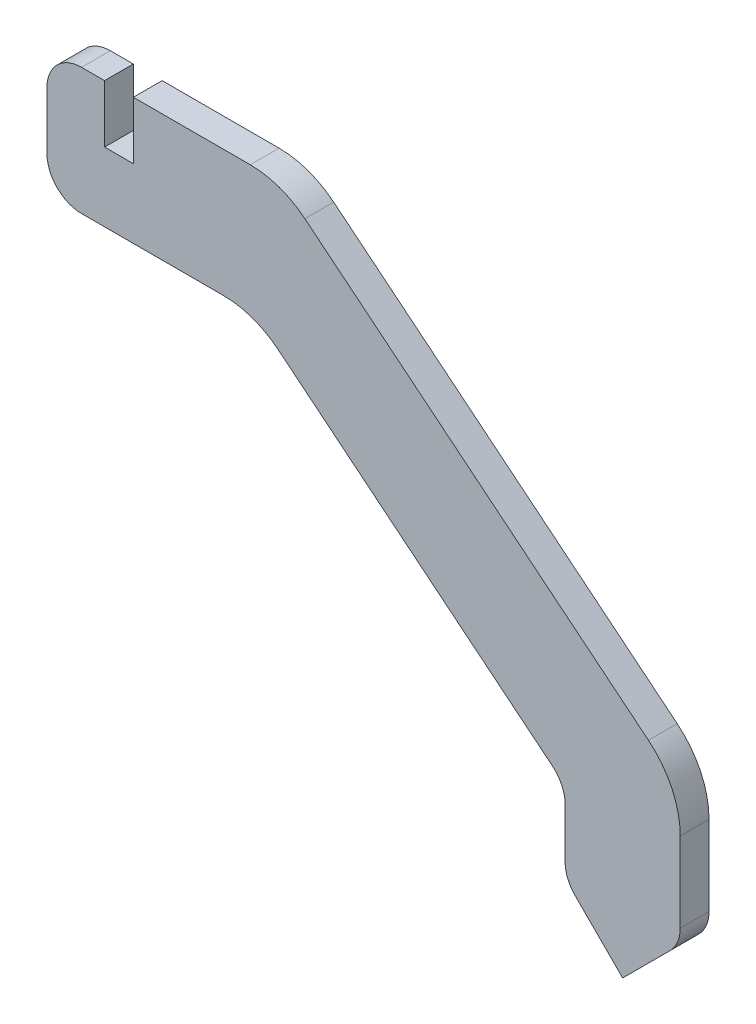
SolidWorks part; units mm, degrees
material "PBT General Purpose"
ref_plane "Front Plane" through (0, 0, 0) normal (0, 0, 1) x (1, 0, 0)
ref_plane "Top Plane" through (0, 0, 0) normal (0, 1, 0) x (1, 0, 0)
ref_plane "Right Plane" through (0, 0, 0) normal (1, 0, 0) x (0, 0, -1)
sketch "frame_outline" plane through (0, 0, 0) normal (0, 0, 1) x (1, 0, 0)
  line L127 (0, 0) -> (0, 1.1)
  line L128 (0, 1.1) -> (0.5, 1.1)
  line L129 (0.5, 1.1) -> (0.5, 0.6)
  line L130 (0.5, 0.6) -> (0.75, 0.6)
  line L131 (0.75, 0.6) -> (0.75, 1.1)
  line L132 (0.75, 1.1) -> (2.0331, 1.1)
  line L133 (2.0331, 1.1) -> (5.5, -1.7249)
  line L134 (5.5, -1.7249) -> (5.5, -2.9)
  line L135 (5.5, -2.9) -> (5, -3.4)
  line L136 (5, -3.4) -> (4.5, -2.9)
  line L137 (4.5, -2.9) -> (4.5, -2.2)
  line L138 (4.5, -2.2) -> (1.8, 0)
  line L139 (1.8, 0) -> (0, 0)
  dimension "D1" = 0.25
  dimension "D2" = 0.5
  dimension "D3" = 0.6
  dimension "D4" = 0.5
  dimension "D5" = 5
  dimension "D6" = 3.4
  dimension "D7" = 1
  dimension "D8" = 1
  dimension "D9" = 0.7
  dimension "D10" = 1.8
extrude "Boss-Extrude1" add sketch "frame_outline" along normal mid plane 0.25
fillet "Fillet1" radius 0.3 5 edges at (5.5, -2.9, 0) (4.5, -2.9, 0) (0, 1.1, 0) (4.5, -2.2, 0) (0, 0, 0)
fillet "Fillet2" radius 0.75 3 edges at (5.5, -1.7249, 0) (2.0331, 1.1, 0) (1.8, 0, 0)
equation "\"t\"= 0.25'thickness of the sheets"
equation "\"t_cf\" = 0.115'thickness of single carbon fiber layer"
equation "\"t_kapton\" = 0.025'thickness of single Kapton flex layer"
equation "\"t_fr4\" = 0.1'thickness of FR4 with copper layer"
equation "\"joint_flex\"= 0.1'Width of flextures gap"
equation "\"joint_flex_eff\"= 0.02'Width of flecture after castelation"
equation "\"joint_fold\"= 0.2'Width of folding joints for 90deg fold"
equation "\"gap_tolerance\"= 0.002'Width to have interfecence fit between carbon fiber inserts"
equation "\"assemble_angle\"= 90'Angle of assembly parts"
equation "\"D1@Boss-Extrude1\"=\"t\""
equation "\"link_lift\"= 0.5'Actuation linkage amplification for the lift motion"
equation "\"link_swing\"= 0.45'Actuation linkage amplification for the swing motion"
equation "\"D1@frame_outline\"=\"t\""
